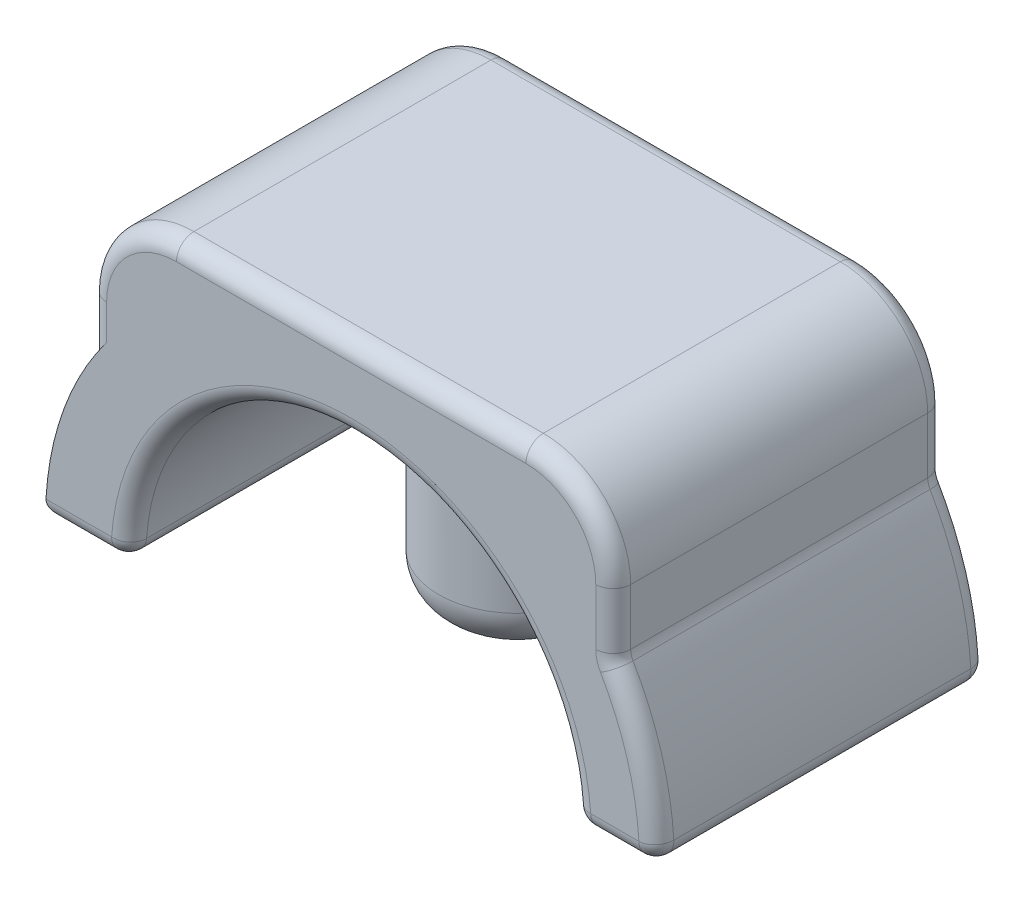
SolidWorks part; units mm, degrees
ref_plane "Front Plane" through (0, 0, 0) normal (0, 0, 1) x (1, 0, 0)
ref_plane "Top Plane" through (0, 0, 0) normal (0, 1, 0) x (1, 0, 0)
ref_plane "Right Plane" through (0, 0, 0) normal (1, 0, 0) x (0, 0, -1)
sketch "Sketch2" plane through (0, 0, 0) normal (0, 0, 1) x (1, 0, 0)
  line L0 (-3.5, 0) -> (-2.55, 0)
  line L1 (2.55, 0) -> (3.5, 0)
  line L2 (0, 3.5) -> (-2, 3.5)
  line L3 (-3, 2.5) -> (-3, 1.8028)
  line L4 (0, 3.5) -> (2, 3.5)
  line L6 (3, 2.5) -> (3, 1.8028)
  arc A0 (2.55, 0) -> (-2.55, 0) centre (0, 0) ccw
  arc A1 (3.5, 0) -> (3, 1.8028) centre (0, 0) ccw
  arc A2 (-3, 1.8028) -> (-3.5, 0) centre (0, 0) ccw
  arc A3 (3, 2.5) -> (2, 3.5) centre (2, 2.5) ccw
  arc A4 (-2, 3.5) -> (-3, 2.5) centre (-2, 2.5) ccw
  point P13 (3, 3.5)
  point P16 (-3, 3.5)
  dimension "D1" = 5.1
  dimension "D2" = 7
  dimension "D5" = 1
  dimension "D3" = 3
  dimension "D4" = 3
extrude "Boss-Extrude1" add sketch "Sketch2" along normal blind 3.8
sketch "Sketch3" plane through (0, 0, 0) normal (0, 1, 0) x (1, 0, 0)
  line L0 (2.55, -1.9) -> (-2.55, -1.9) construction
  line L1 (2.55, -3.8) -> (2.55, 0) construction
  line L2 (-2.55, -3.8) -> (-2.55, 0) construction
  circle A0 centre (0, -1.9) radius 0.9
  dimension "D1" = 1.8
extrude "Boss-Extrude2" add sketch "Sketch3" along normal blind 3
fillet "Fillet1" radius 0.5 1 edges at (0, 0, 2.8)
fillet "Fillet3" radius 0.2 24 edges at (-3.025, 0, 3.8) (-3.025, 0, 0) (3.3727, 0.9354, 3.8) (3.3727, 0.9354, 0) (3.025, 0, 3.8) (3.5, 0, 1.9) (3.025, 0, 0) (-0.1467, 2.5458, 2.788) (-2.55, 0, 1.9) (0, 2.55, 3.8) (2.55, 0, 1.9) (0, 2.55, 0) (-3, 2.1514, 3.8) (-3, 2.1514, 0) (-2.7071, 3.2071, 3.8) (-2.7071, 3.2071, 0) (0, 3.5, 3.8) (0, 3.5, 0) (2.7071, 3.2071, 3.8) (2.7071, 3.2071, 0) (3, 2.1514, 3.8) (3, 2.1514, 0) (-3.5, 0, 1.9) (3, 1.8028, 1.9)
